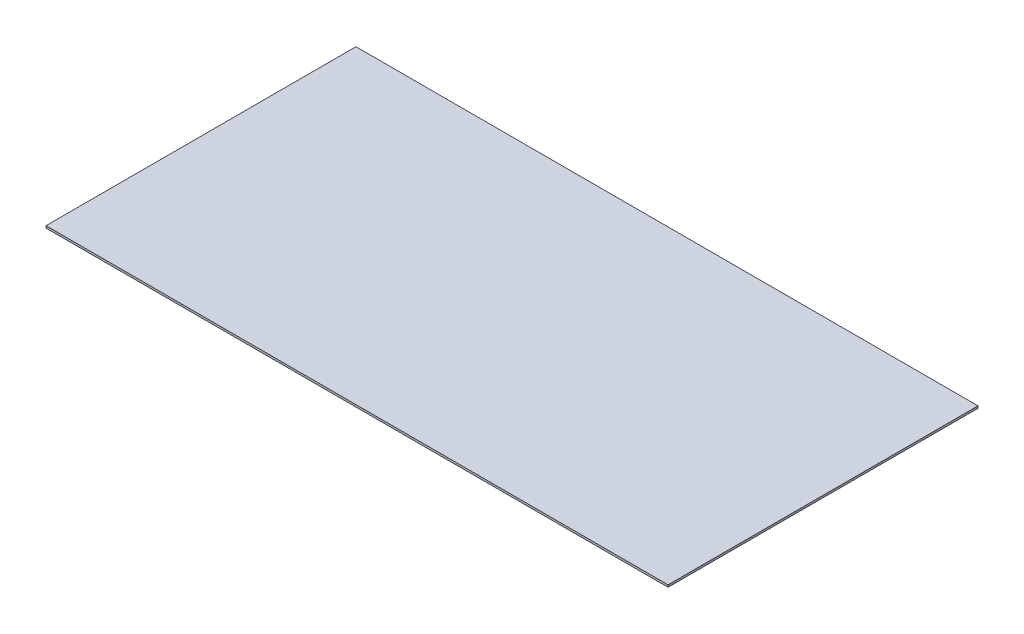
SolidWorks part; units mm, degrees
ref_plane "Front Plane" through (0, 0, 0) normal (0, 0, 1) x (1, 0, 0)
ref_plane "Top Plane" through (0, 0, 0) normal (0, 1, 0) x (1, 0, 0)
ref_plane "Right Plane" through (0, 0, 0) normal (1, 0, 0) x (0, 0, -1)
sketch "Sketch1" plane through (0, 0, 0) normal (0, 1, 0) x (1, 0, 0)
  line L0 (-437.5, 218) -> (437.5, 218)
  line L1 (-437.5, 218) -> (-437.5, -218)
  line L2 (-437.5, -218) -> (437.5, -218)
  line L3 (437.5, 218) -> (437.5, -218)
extrude "Boss-Extrude1" add sketch "Sketch1" along normal blind 3
